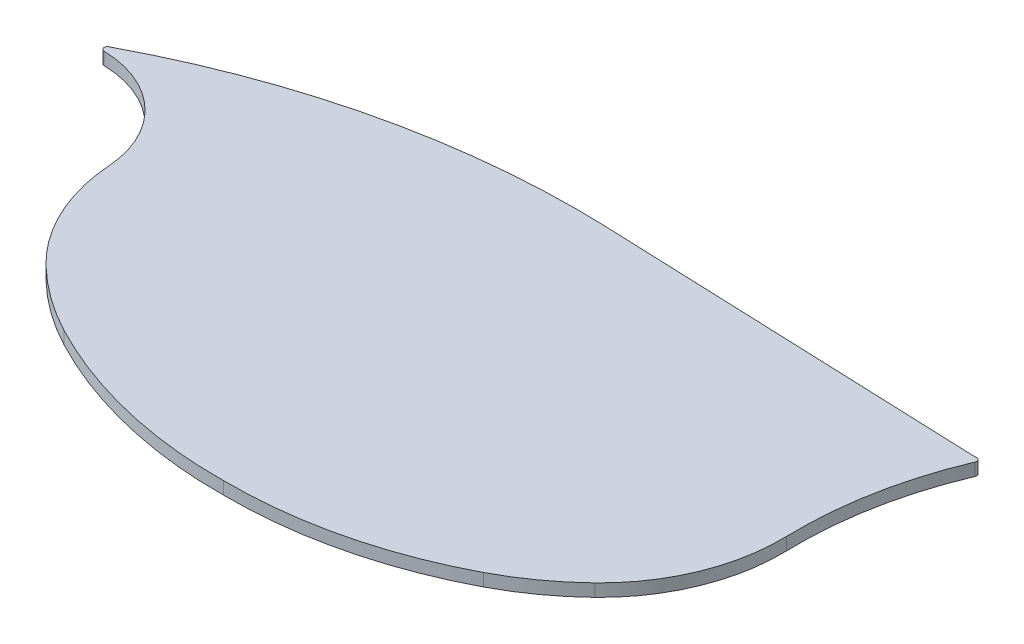
SolidWorks part; units mm, degrees
ref_plane "Front Plane" through (0, 0, 0) normal (0, 0, 1) x (1, 0, 0)
ref_plane "Top Plane" through (0, 0, 0) normal (0, 1, 0) x (1, 0, 0)
ref_plane "Right Plane" through (0, 0, 0) normal (1, 0, 0) x (0, 0, -1)
sketch "Sketch1" plane through (0, 0, 0) normal (0, 1, 0) x (1, 0, 0)
  line L6 (125.3344, 60.7056) -> (34.689, 64.1971)
  line L7 (125.3421, 60.9054) -> (34.6967, 64.397)
  line L8 (125.3421, 60.9054) -> (34.6967, 64.397) construction
  arc A89 (34.689, 64.1971) -> (-62.0515, 42.1534) centre (27.3316, -126.8131) ccw
  arc A90 (-62.0515, 42.1534) -> (-61.8694, 40.5786) centre (-61.8533, 41.3784) ccw
  arc A91 (-37.6013, 17.4999) -> (-61.8694, 40.5786) centre (-62.3702, 15.7532) ccw
  arc A92 (-37.6013, 17.4999) -> (-24.4127, -10.7507) centre (5.8076, 20.5613) ccw
  arc A93 (-24.4127, -10.7507) -> (-8.9722, -21.9015) centre (22.2519, 37.5995) ccw
  arc A94 (-8.9722, -21.9015) -> (41.1324, -33.9453) centre (39.9254, 71.2784) ccw
  arc A95 (41.1324, -33.9453) -> (91.2371, -21.9015) centre (42.3395, 71.2784) ccw
  arc A96 (91.2371, -21.9015) -> (106.6775, -10.7507) centre (60.013, 37.5995) ccw
  arc A97 (106.6775, -10.7507) -> (119.9307, 21.7139) centre (76.517, 20.4993) ccw
  arc A98 (127.05, 59.6201) -> (119.9307, 21.7139) centre (210.8595, 24.2577) ccw
  arc A99 (127.05, 59.6201) -> (126.2428, 60.728) centre (126.3129, 59.9311) ccw
  arc A100 (125.3344, 60.7056) -> (126.2428, 60.728) centre (125.6116, 67.9003) ccw
  arc A101 (125.3421, 60.9054) -> (126.2253, 60.9272) centre (125.6116, 67.9003) ccw
  arc A102 (34.6967, 64.397) -> (-62.1252, 42.3407) centre (27.3316, -126.8131) ccw
  arc A103 (-62.1252, 42.3407) -> (-61.8734, 40.3786) centre (-61.8533, 41.3784) ccw
  arc A104 (-37.8008, 17.4859) -> (-61.8734, 40.3786) centre (-62.3702, 15.7532) ccw
  arc A105 (-37.8008, 17.4859) -> (-24.5516, -10.8946) centre (5.8076, 20.5613) ccw
  arc A106 (-24.5516, -10.8946) -> (-9.0652, -22.0786) centre (22.2519, 37.5995) ccw
  arc A107 (-9.0652, -22.0786) -> (41.1324, -34.1453) centre (39.9254, 71.2784) ccw
  arc A108 (41.1324, -34.1453) -> (91.33, -22.0786) centre (42.3395, 71.2784) ccw
  arc A109 (91.33, -22.0786) -> (106.8164, -10.8946) centre (60.013, 37.5995) ccw
  arc A110 (106.8164, -10.8946) -> (120.1306, 21.7195) centre (76.517, 20.4993) ccw
  arc A111 (127.2343, 59.5423) -> (120.1306, 21.7195) centre (210.8595, 24.2577) ccw
  arc A112 (127.2343, 59.5423) -> (126.2253, 60.9272) centre (126.3129, 59.9311) ccw
  arc A113 (125.3421, 60.9054) -> (126.2253, 60.9272) centre (125.6116, 67.9003) ccw construction
  arc A114 (34.6967, 64.397) -> (-62.1252, 42.3407) centre (27.3316, -126.8131) ccw construction
  arc A115 (-62.1252, 42.3407) -> (-61.8734, 40.3786) centre (-61.8533, 41.3784) ccw construction
  arc A116 (-37.8008, 17.4859) -> (-61.8734, 40.3786) centre (-62.3702, 15.7532) ccw construction
  arc A117 (-37.8008, 17.4859) -> (-24.5516, -10.8946) centre (5.8076, 20.5613) ccw construction
  arc A118 (-24.5516, -10.8946) -> (-9.0652, -22.0786) centre (22.2519, 37.5995) ccw construction
  arc A119 (-9.0652, -22.0786) -> (41.1324, -34.1453) centre (39.9254, 71.2784) ccw construction
  arc A120 (41.1324, -34.1453) -> (91.33, -22.0786) centre (42.3395, 71.2784) ccw construction
  arc A121 (91.33, -22.0786) -> (106.8164, -10.8946) centre (60.013, 37.5995) ccw construction
  arc A122 (106.8164, -10.8946) -> (120.1306, 21.7195) centre (76.517, 20.4993) ccw construction
  arc A123 (127.2343, 59.5423) -> (120.1306, 21.7195) centre (210.8595, 24.2577) ccw construction
  arc A124 (127.2343, 59.5423) -> (126.2253, 60.9272) centre (126.3129, 59.9311) ccw construction
  dimension "D1" = 0
  dimension "D2" = 0.2
extrude "Boss-Extrude1" add sketch "Sketch1" along normal blind 3
